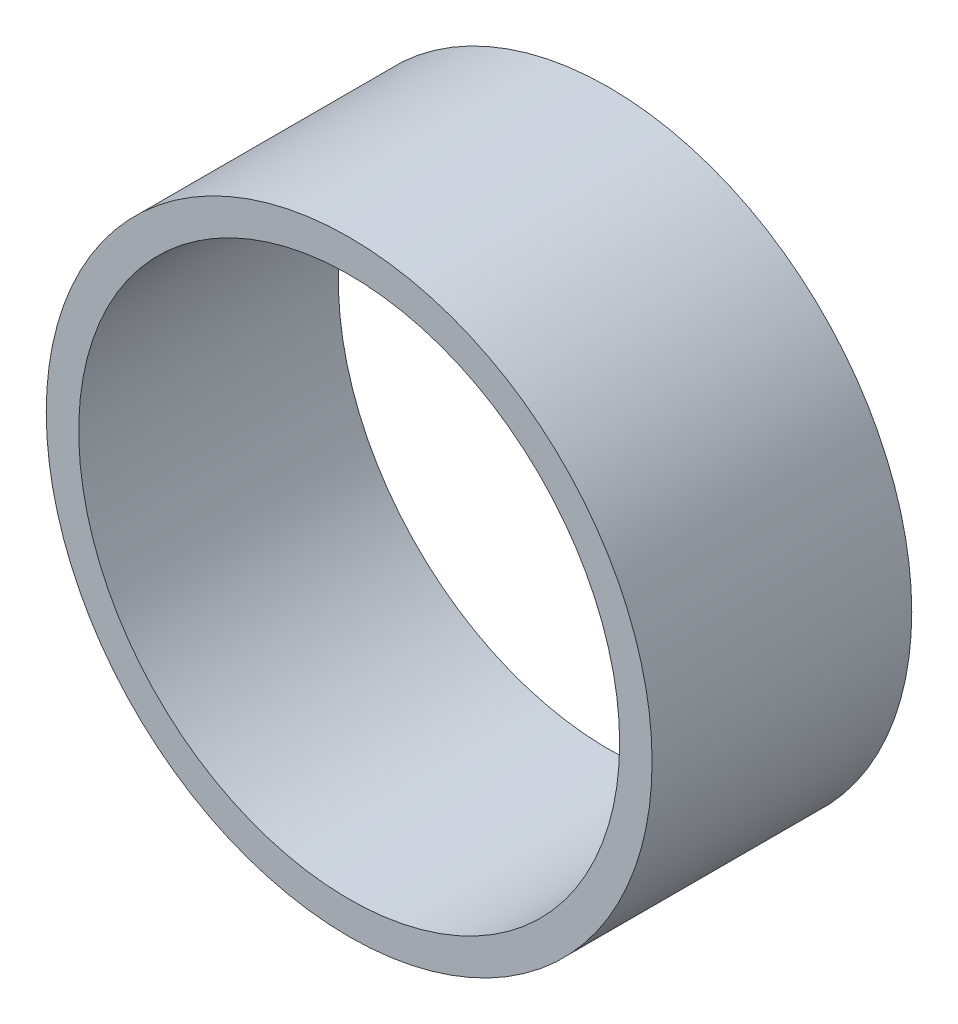
SolidWorks part; units mm, degrees
ref_plane "Front Plane" through (0, 0, 0) normal (0, 0, 1) x (1, 0, 0)
ref_plane "Top Plane" through (0, 0, 0) normal (0, 1, 0) x (1, 0, 0)
ref_plane "Right Plane" through (0, 0, 0) normal (1, 0, 0) x (0, 0, -1)
sketch "Sketch1" plane through (0, 0, 0) normal (0, 0, 1) x (1, 0, 0)
  circle A0 centre (0, 0) radius 12.5
  circle A1 centre (0, 0) radius 14
  dimension "D1" = 25
  dimension "D2" = 28
extrude "Boss-Extrude1" add sketch "Sketch1" along normal blind 12
